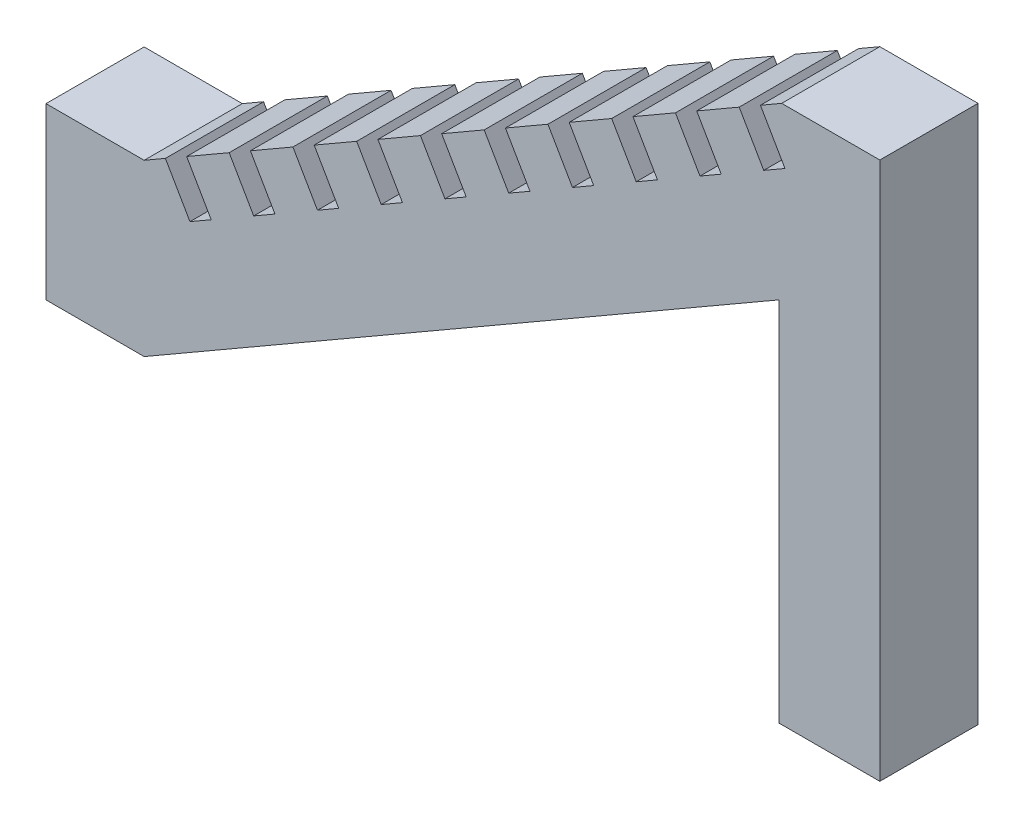
SolidWorks part; units mm, degrees
ref_plane "Plan de face" through (0, 0, 0) normal (0, 0, 1) x (1, 0, 0)
ref_plane "Plan de dessus" through (0, 0, 0) normal (0, 1, 0) x (1, 0, 0)
ref_plane "Plan de droite" through (0, 0, 0) normal (1, 0, 0) x (0, 0, -1)
other "Centre de masse"
sketch "Esquisse2" plane through (0, 0, 0) normal (0, 0, 1) x (1, 0, 0)
  line L0 (-73.926, 0) -> (187.7314, 0) construction
  line L4 (0, 0) -> (-20, 0)
  line L5 (-20, 0) -> (-20, 34.641)
  line L6 (0, 0) -> (0, 39.7837) construction
  line L17 (0, 34.641) -> (-20, 34.641)
  line L22 (129.3788, 74.6969) -> (114.3788, 100.6776) construction
  line L25 (0, 34.641) -> (142.9244, 117.1584) construction
  line L31 (0, 34.641) -> (129.9038, 109.641)
  line L33 (129.9038, 109.641) -> (149.9038, 109.641)
  line L34 (149.9038, 109.641) -> (149.9038, 0)
  line L35 (149.9038, 0) -> (129.3788, 0)
  line L36 (0, 0) -> (129.3788, 74.6969)
  line L37 (129.3788, 0) -> (129.3788, 74.6969)
  dimension "D1" = 30
  dimension "D2" = 90
  dimension "D3" = 30
  dimension "D4" = 90
  dimension "D5" = 20
  dimension "D6" = 30
  dimension "D7" = 90
  dimension "D8" = 150
  dimension "D9" = 20
extrude "Boss.-Extru.2" add sketch "Esquisse2" along normal blind 20
sketch "Esquisse4" plane through (-15, 25.9808, 0) normal (-0.5, 0.866, 0) x (0.866, 0.5, 0)
  line L0 (3.0796, -20) -> (185.7562, -20) construction
  line L6 (167.3205, 0) -> (17.3205, 0) construction
  line L7 (22.3205, -20) -> (27.3205, -20)
  line L10 (22.3205, -20) -> (22.3205, 0)
  line L11 (22.3205, 0) -> (27.3205, 0)
  line L12 (27.3205, -20) -> (27.3205, 0)
  line L13 (17.3205, -20) -> (17.3205, 0) construction
  line L15 (37.3205, -20) -> (42.3205, -20)
  line L16 (37.3205, -20) -> (37.3205, 0)
  line L17 (37.3205, 0) -> (42.3205, 0)
  line L18 (42.3205, -20) -> (42.3205, 0)
  line L19 (52.3205, -20) -> (57.3205, -20)
  line L20 (52.3205, -20) -> (52.3205, 0)
  line L21 (52.3205, 0) -> (57.3205, 0)
  line L22 (57.3205, -20) -> (57.3205, 0)
  line L23 (67.3205, -20) -> (72.3205, -20)
  line L24 (67.3205, -20) -> (67.3205, 0)
  line L25 (67.3205, 0) -> (72.3205, 0)
  line L26 (72.3205, -20) -> (72.3205, 0)
  line L27 (82.3205, -20) -> (87.3205, -20)
  line L28 (82.3205, -20) -> (82.3205, 0)
  line L29 (82.3205, 0) -> (87.3205, 0)
  line L30 (87.3205, -20) -> (87.3205, 0)
  line L31 (97.3205, -20) -> (102.3205, -20)
  line L32 (97.3205, -20) -> (97.3205, 0)
  line L33 (97.3205, 0) -> (102.3205, 0)
  line L34 (102.3205, -20) -> (102.3205, 0)
  line L35 (112.3205, -20) -> (117.3205, -20)
  line L36 (112.3205, -20) -> (112.3205, 0)
  line L37 (112.3205, 0) -> (117.3205, 0)
  line L38 (117.3205, -20) -> (117.3205, 0)
  line L51 (162.3205, 0) -> (167.3205, 0) construction
  line L52 (127.3205, -20) -> (132.3205, -20)
  line L53 (127.3205, -20) -> (127.3205, 0)
  line L54 (127.3205, 0) -> (132.3205, 0)
  line L55 (132.3205, -20) -> (132.3205, 0)
  line L56 (142.3205, -20) -> (147.3205, -20)
  line L57 (142.3205, -20) -> (142.3205, 0)
  line L58 (142.3205, 0) -> (147.3205, 0)
  line L59 (147.3205, -20) -> (147.3205, 0)
  line L60 (157.3205, -20) -> (162.3205, -20)
  line L61 (157.3205, -20) -> (157.3205, 0)
  line L62 (157.3205, 0) -> (162.3205, 0)
  line L63 (162.3205, -20) -> (162.3205, 0)
  point P33 (102.3205, -10)
  dimension "D1" = 5
  dimension "D2" = 5
  dimension "D3" = 10
  dimension "D4" = 5
  dimension "D5" = 10
  dimension "D6" = 5
  dimension "D7" = 10
  dimension "D8" = 5
  dimension "D9" = 10
  dimension "D10" = 5
  dimension "D11" = 10
  dimension "D12" = 5
  dimension "D13" = 10
  dimension "D14" = 5
  dimension "D15" = 10
  dimension "D16" = 5
  dimension "D17" = 10
  dimension "D18" = 5
  dimension "D19" = 10
  dimension "D20" = 5
  dimension "D21" = 150
extrude "Enlèv. mat.-Extru.1" cut sketch "Esquisse4" against normal blind 10
